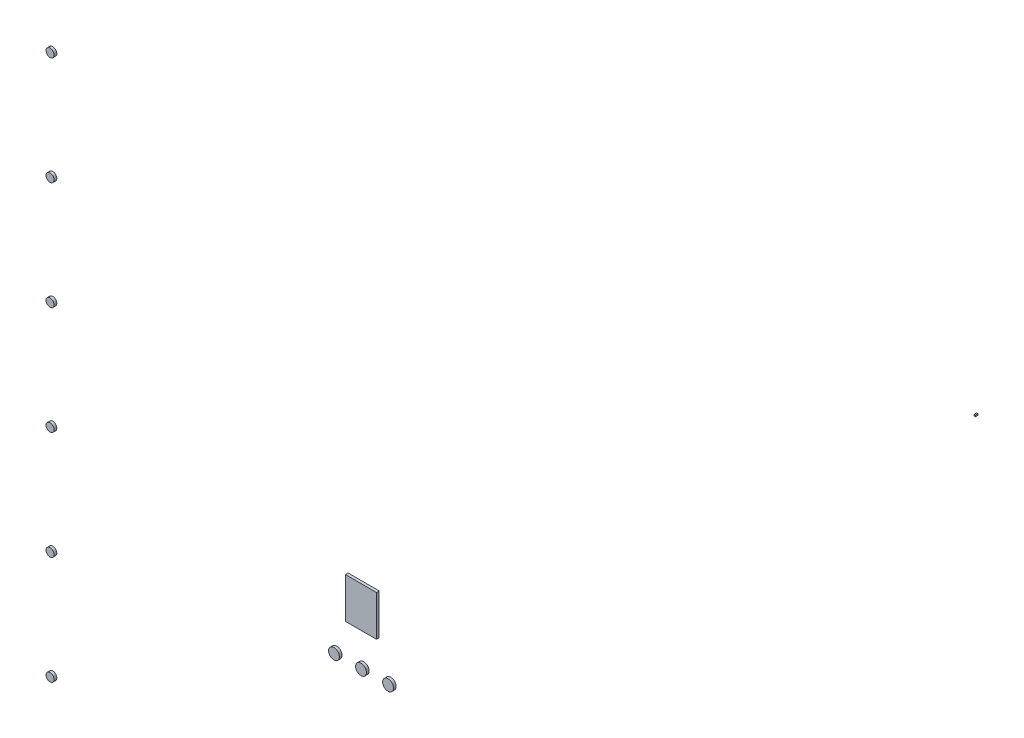
SolidWorks part; units mm, degrees
ref_plane "Front Plane" through (0, 0, 0) normal (0, 0, 1) x (1, 0, 0)
ref_plane "Top Plane" through (0, 0, 0) normal (0, 1, 0) x (1, 0, 0)
ref_plane "Right Plane" through (0, 0, 0) normal (1, 0, 0) x (0, 0, -1)
sketch "Sketch1" plane through (0, 0, 0) normal (0, 0, 1) x (1, 0, 0)
  line L0 (481.5, 204.6) -> (481.5, 234.6) construction
  line L1 (924.4, 569.6) -> (923.4, 569.6)
  line L2 (924.4, 569.6) -> (924.4, 568.6)
  line L3 (924.4, 568.6) -> (923.4, 568.6)
  line L4 (10, -30) -> (924.4, -30)
  line L5 (924.4, -30) -> (924.4, 569.6)
  line L6 (924.4, 569.6) -> (10, 569.6)
  line L7 (10, 569.6) -> (10, -30)
  line L8 (10, -30) -> (924.4, -30)
  line L9 (924.4, 568.6) -> (924.4, 569.6)
  line L10 (924.4, 569.6) -> (923.4, 569.6)
  line L11 (10, 569.6) -> (10, -30)
  line L12 (923.4, 569.6) -> (923.4, 568.6)
  line L13 (458.5, 204.6) -> (481.5, 204.6) construction
  line L14 (458.5, 234.6) -> (458.5, 204.6) construction
  line L15 (481.5, 234.6) -> (458.5, 234.6) construction
  line L16 (481.5, 204.6) -> (481.5, 234.6)
  line L17 (458.5, 204.6) -> (481.5, 204.6)
  line L18 (458.5, 234.6) -> (458.5, 204.6)
  line L19 (481.5, 234.6) -> (458.5, 234.6)
  circle A0 centre (450, 179.6) radius 4 construction
  circle A1 centre (470, 179.6) radius 4 construction
  circle A2 centre (490, 179.6) radius 4 construction
  circle A3 centre (450, 179.6) radius 4
  circle A4 centre (470, 179.6) radius 4
  circle A5 centre (490, 179.6) radius 4
  circle A6 centre (240, 459.6) radius 3 construction
  circle A7 centre (240, 379.6) radius 3 construction
  circle A8 centre (240, 299.6) radius 3 construction
  circle A9 centre (240, 219.6) radius 3 construction
  circle A10 centre (240, 139.6) radius 3 construction
  circle A11 centre (240, 59.6) radius 3 construction
  circle A12 centre (240, 459.6) radius 3
  circle A13 centre (240, 379.6) radius 3
  circle A14 centre (240, 299.6) radius 3
  circle A15 centre (240, 219.6) radius 3
  circle A16 centre (240, 139.6) radius 3
  circle A17 centre (240, 59.6) radius 3
  dimension "D2" = 1
  dimension "D3" = 1
  dimension "D1" = 0
extrude "Boss-Extrude1" add sketch "Sketch1" along normal blind 2 contours A14 | A13 | A12 | A15 | A16 | A17 | L16 L19 L18 L17 | A5 | A4 | A3 | L1 L12 L3 L2
